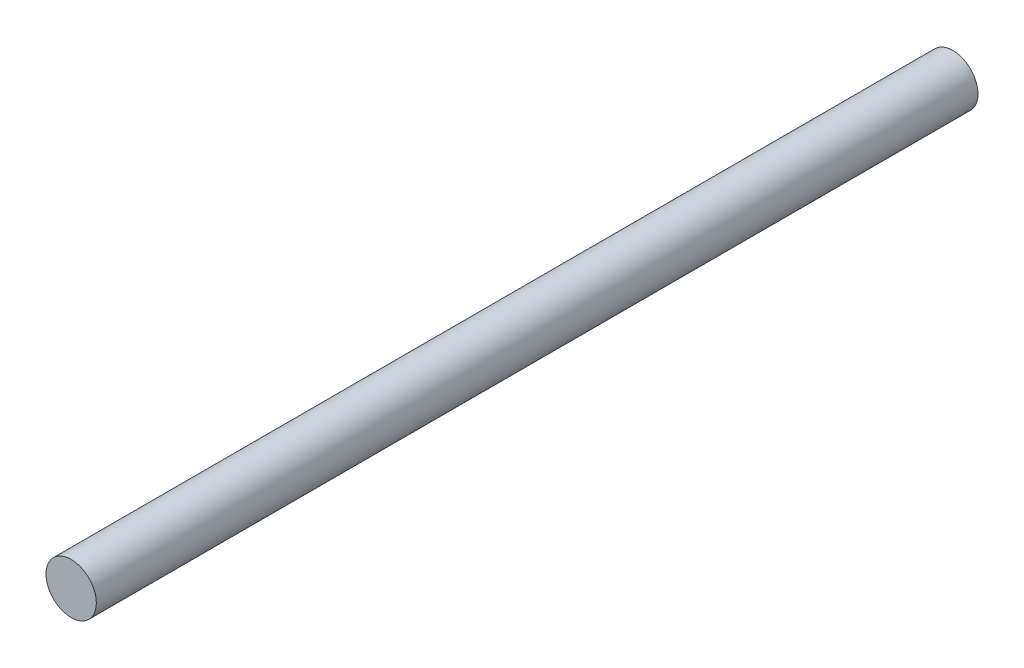
SolidWorks part; units mm, degrees
ref_plane "Front Plane" through (0, 0, 0) normal (0, 0, 1) x (1, 0, 0)
ref_plane "Top Plane" through (0, 0, 0) normal (0, 1, 0) x (1, 0, 0)
ref_plane "Right Plane" through (0, 0, 0) normal (1, 0, 0) x (0, 0, -1)
sketch "Sketch1" plane through (0, 0, 0) normal (0, 0, 1) x (1, 0, 0)
  circle A0 centre (0, 0) radius 1
  dimension "D1" = 2
extrude "Boss-Extrude1" add sketch "Sketch1" along normal blind 35
